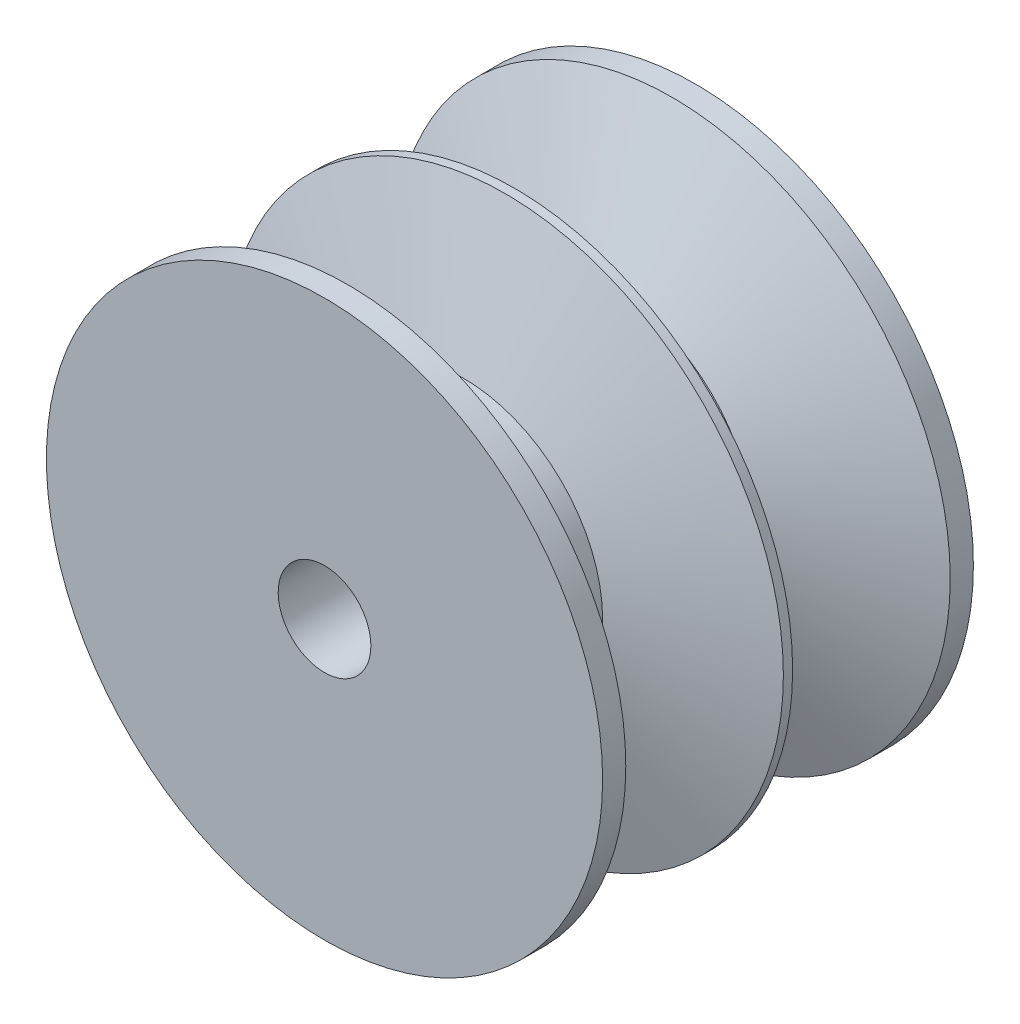
SolidWorks part; units mm, degrees
ref_plane "Front Plane" through (0, 0, 0) normal (0, 0, 1) x (1, 0, 0)
ref_plane "Top Plane" through (0, 0, 0) normal (0, 1, 0) x (1, 0, 0)
ref_plane "Right Plane" through (0, 0, 0) normal (1, 0, 0) x (0, 0, -1)
sketch "Sketch1" plane through (0, 0, 0) normal (1, 0, 0) x (0, 0, -1)
  line L0 (-8, 0) -> (8, 0)
  line L1 (-8, 0) -> (-8, 12)
  line L2 (-8, 12) -> (-7, 12)
  line L3 (-4.5, 6) -> (-2, 6)
  line L4 (2, 6) -> (4.5, 6)
  line L5 (0.2, 12) -> (2, 6)
  line L6 (7, 12) -> (4.5, 6)
  line L7 (-0.2, 12) -> (-2, 6)
  line L8 (-7, 12) -> (-4.5, 6)
  line L9 (7, 12) -> (8, 12)
  line L10 (-0.2, 12) -> (0.2, 12)
  line L11 (8, 12) -> (8, 0)
  dimension "D1" = 16
  dimension "D2" = 12
  dimension "D3" = 8
  dimension "D4" = 6
  dimension "D5" = 0.2
  dimension "D6" = 0.2
  dimension "D7" = 2
  dimension "D8" = 2
  dimension "D9" = 1
  dimension "D10" = 3.5
  dimension "D11" = 3.5
  dimension "D12" = 1
revolve "Revolve1" add sketch "Sketch1" angle 360 about L0
sketch "Sketch3" plane through (0, 0, -8) normal (0, 0, -1) x (-1, 0, 0)
  line L0 (-1.3229, 1.5) -> (1.3229, 1.5)
  arc A0 (-1.3229, 1.5) -> (1.3229, 1.5) centre (0, 0) ccw
  dimension "D1" = 4
  dimension "D2" = 1.5
extrude "Cut-Extrude1" cut sketch "Sketch3" against normal blind 12
sketch "Sketch4" plane through (0, 0, 8) normal (0, 0, 1) x (1, 0, 0)
  circle A0 centre (0, 0) radius 2
  dimension "D1" = 4
extrude "Cut-Extrude2" cut sketch "Sketch4" against normal blind 4
